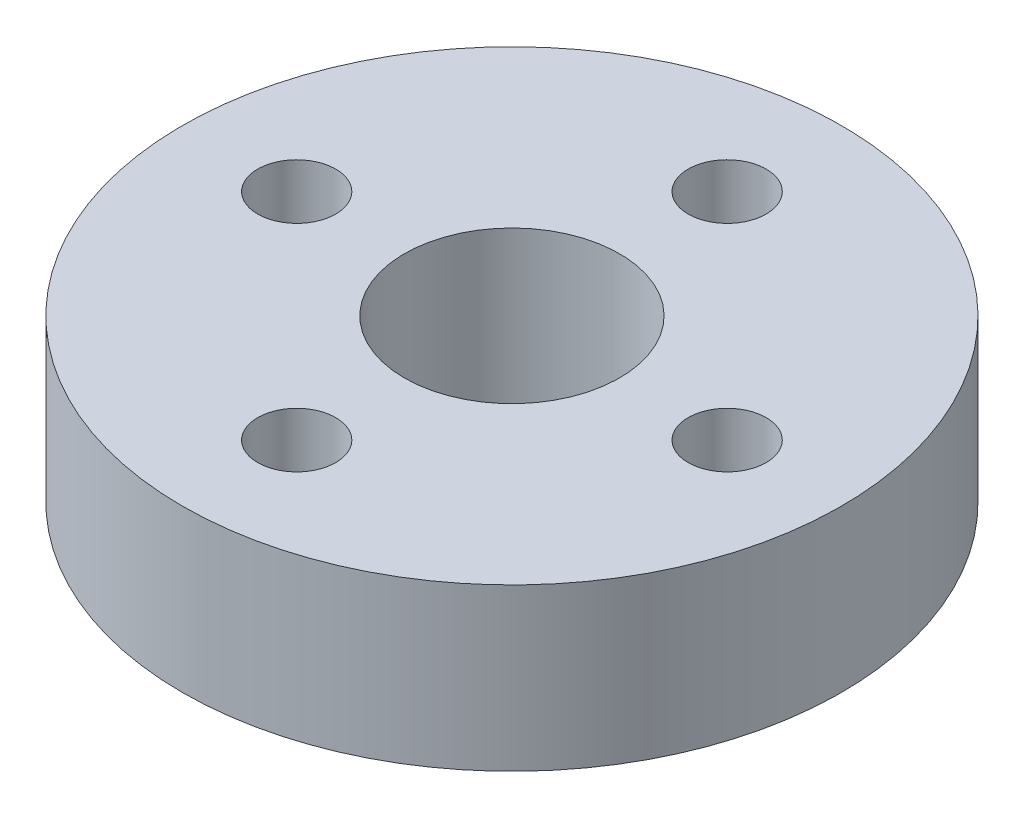
SolidWorks part; units mm, degrees
ref_plane "前视基准面" through (0, 0, 0) normal (0, 0, 1) x (1, 0, 0)
ref_plane "上视基准面" through (0, 0, 0) normal (0, 1, 0) x (1, 0, 0)
ref_plane "右视基准面" through (0, 0, 0) normal (1, 0, 0) x (0, 0, -1)
sketch "草图1" plane through (0, 0, 0) normal (0, 1, 0) x (1, 0, 0)
  line L1 (8, 0) -> (0, 8) construction
  line L2 (0, 8) -> (-8, 0) construction
  line L3 (-8, 0) -> (0, -8) construction
  line L4 (0, -8) -> (8, 0) construction
  circle A0 centre (0, 0) radius 12.25
  circle A1 centre (0, 0) radius 4
  circle A2 centre (0, 0) radius 8 construction
  circle A3 centre (0, 0) radius 5.6569 construction
  circle A4 centre (0, 8) radius 1.45
  circle A5 centre (8, 0) radius 1.45
  circle A6 centre (0, -8) radius 1.45
  circle A7 centre (-8, 0) radius 1.45
  point P14 (0, 0)
  point P15 (0, 8)
  dimension "D1" = 24.5
  dimension "D2" = 8
  dimension "D3" = 16
  dimension "D4" = 2.9
extrude "凸台-拉伸1" add sketch "草图1" along normal blind 6
